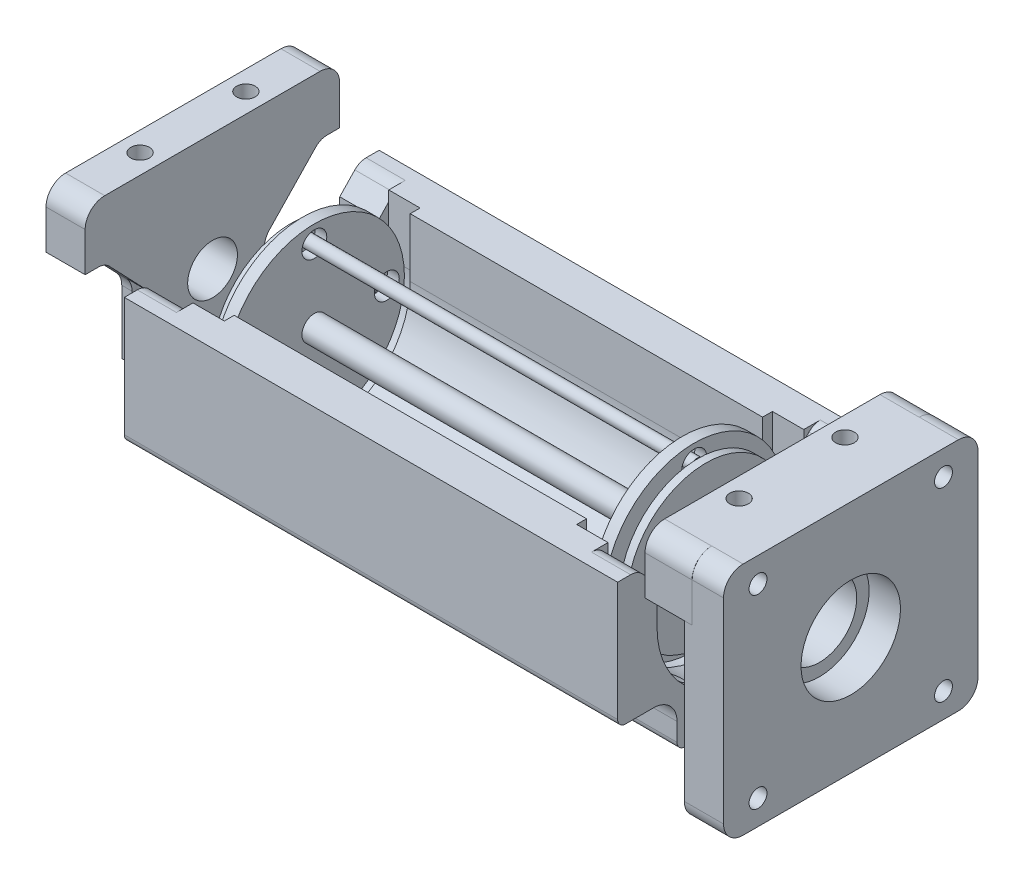
SolidWorks part; units mm, degrees
ref_plane "Front Plane" through (0, 0, 0) normal (0, 0, 1) x (1, 0, 0)
ref_plane "Top Plane" through (0, 0, 0) normal (0, 1, 0) x (1, 0, 0)
ref_plane "Right Plane" through (0, 0, 0) normal (1, 0, 0) x (0, 0, -1)
ref_plane "Plane1" through (-50, 0, 0) normal (1, 0, 0) x (0, 0, -1)
sketch "Sketch2" plane through (-50, 0, 0) normal (1, 0, 0) x (0, 0, -1)
  line L0 (0, 0) -> (0, 1.0694) construction
  circle A0 centre (0, 0) radius 3.175
  circle A1 centre (0, 18.5125) radius 1.5875 construction
  circle A2 centre (0, 18.5125) radius 3.175
  circle A3 centre (0, 0) radius 23
  circle A4 centre (-18.5125, 0) radius 1.5875 construction
  circle A5 centre (-18.5125, 0) radius 3.175
  circle A6 centre (0, -18.5125) radius 1.5875 construction
  circle A7 centre (0, -18.5125) radius 3.175
  circle A8 centre (18.5125, 0) radius 1.5875 construction
  circle A9 centre (18.5125, 0) radius 3.175
  dimension "D1" = 6.35
  dimension "D2" = 3.175
  dimension "D3" = 6.35
  dimension "D4" = 46
extrude "Boss-Extrude2" add sketch "Sketch2" along normal blind 3 separate body
ref_plane "Plane2" through (45, 0, 0) normal (1, 0, 0) x (0, 0, -1)
sketch "Sketch3" plane through (45, 0, 0) normal (1, 0, 0) x (0, 0, -1)
  line L0 (-22.4812, 0) -> (-22.4812, 15)
  line L1 (22.4812, 0) -> (22.4812, 15)
  line L2 (-23.371, -17.371) -> (-30.54, -17.371)
  line L3 (0, 0) -> (0, 31.7138) construction
  line L4 (-15.371, -30) -> (15.371, -30)
  line L5 (-17.371, -23.371) -> (-17.371, -28)
  line L6 (17.371, -23.371) -> (17.371, -28)
  line L7 (23.371, -17.371) -> (30, -17.371)
  line L8 (-32.54, 15) -> (-32.54, -15.371)
  line L9 (22.4812, 15) -> (32.54, 15)
  line L10 (-22.4812, 15) -> (-32.54, 15)
  line L11 (32.54, 15) -> (32.54, -15.371)
  line L13 (30.54, -17.371) -> (30, -17.371)
  arc A0 (-22.4812, 0) -> (22.4812, 0) centre (0, 0) ccw
  arc A1 (-23.371, -17.371) -> (-17.371, -23.371) centre (-23.371, -23.371) cw
  arc A2 (17.371, -23.371) -> (23.371, -17.371) centre (23.371, -23.371) cw
  arc A3 (-30.54, -17.371) -> (-32.54, -15.371) centre (-30.54, -15.371) cw
  arc A4 (32.54, -15.371) -> (30.54, -17.371) centre (30.54, -15.371) cw
  arc A5 (-17.371, -28) -> (-15.371, -30) centre (-15.371, -28) ccw
  arc A6 (17.371, -28) -> (15.371, -30) centre (15.371, -28) cw
  dimension "D1" = 6
  dimension "D2" = 6
  dimension "D3" = 2
  dimension "D4" = 2
  dimension "D5" = 2
extrude "Boss-Extrude3" add sketch "Sketch3" against normal blind 90 separate body
ref_plane "Plane9" through (-51, 0, 0) normal (1, 0, 0) x (0, 0, -1)
sketch "Sketch16" plane through (-51, 0, 0) normal (1, 0, 0) x (0, 0, -1)
  circle A1 centre (0, 0) radius 3.175
  circle A2 centre (0, 0) radius 20.1
  dimension "D1" = 6.35
extrude "Boss-Extrude7" add sketch "Sketch16" against normal blind 2 separate body
sketch "Sketch21" plane through (0, 0, 0) normal (1, 0, 0) x (0, 0, -1)
  circle A0 centre (-18.5125, 0) radius 1.5875
  circle A1 centre (0, 18.5125) radius 1.5875
  circle A2 centre (18.5125, 0) radius 1.5875
  circle A3 centre (0, -18.5125) radius 1.5875
  dimension "D1" = 4
extrude "Compression_Rods" add sketch "Sketch21" along normal mid plane 101.6 separate body
mirror "Mirror2" about plane through (0, 0, 0) normal (1, 0, 0) of bodies 102 113
ref_plane "Plane13" through (45, 0, 0) normal (1, 0, 0) x (0, 0, -1)
sketch "Sketch24" plane through (45, 0, 0) normal (1, 0, 0) x (0, 0, -1)
  line L0 (-25, 0) -> (-25, 15)
  line L1 (32.54, -15.371) -> (32.54, 15)
  line L2 (0, 0) -> (0, 36.0592) construction
  line L3 (-32.54, 15) -> (-25, 15)
  line L4 (-15.371, -30) -> (15.371, -30)
  line L5 (-17.371, -23.371) -> (-17.371, -28)
  line L6 (17.371, -23.371) -> (17.371, -28)
  line L7 (23.371, -17.371) -> (30.54, -17.371)
  line L8 (32.54, 15) -> (25, 15)
  line L9 (-32.54, -15.371) -> (-32.54, 15)
  line L10 (25, 0) -> (25, 15)
  line L13 (-23.371, -17.371) -> (-30.54, -17.371)
  arc A0 (-25, 0) -> (25, 0) centre (0, 0) ccw
  arc A1 (-17.371, -23.371) -> (-23.371, -17.371) centre (-23.371, -23.371) ccw
  arc A2 (17.371, -23.371) -> (23.371, -17.371) centre (23.371, -23.371) cw
  arc A3 (30.54, -17.371) -> (32.54, -15.371) centre (30.54, -15.371) ccw
  arc A4 (-30.54, -17.371) -> (-32.54, -15.371) centre (-30.54, -15.371) cw
  arc A5 (17.371, -28) -> (15.371, -30) centre (15.371, -28) cw
  arc A8 (-17.371, -28) -> (-15.371, -30) centre (-15.371, -28) ccw
  dimension "D1" = 6
  dimension "D2" = 6
  dimension "D3" = 2
  dimension "D4" = 2
extrude "Boss-Extrude13" add sketch "Sketch24" along normal blind 8 separate body
ref_plane "Plane15" through (70, 0, 0) normal (1, 0, 0) x (0, 0, -1)
sketch "Sketch27" plane through (70, 0, 0) normal (1, 0, 0) x (0, 0, -1)
  line L0 (-5.175, 30) -> (-25, 30)
  line L1 (23.6855, -23.6855) -> (-23.6855, -23.6855) construction
  line L2 (23.6855, -23.6855) -> (23.6855, 23.6855) construction
  line L3 (23.6855, 23.6855) -> (-23.6855, 23.6855) construction
  line L4 (-23.6855, -23.6855) -> (-23.6855, 23.6855) construction
  line L5 (23.6855, -23.6855) -> (-23.6855, 23.6855) construction
  line L6 (23.6855, 23.6855) -> (-23.6855, -23.6855) construction
  line L7 (5.175, 30) -> (25, 30)
  line L8 (-30, 25) -> (-30, -25)
  line L9 (-25, -30) -> (25, -30)
  line L10 (30, 25) -> (30, -25)
  line L11 (-30, 30) -> (30, -30) construction
  line L12 (-30, -30) -> (30, 30) construction
  line L13 (-3.175, 28) -> (-3.175, 20.404)
  line L14 (3.175, 28) -> (3.175, 20.404)
  line L15 (0, 0) -> (0, 18.7836) construction
  circle A0 centre (-23.6855, 23.6855) radius 2.286
  circle A1 centre (23.6855, 23.6855) radius 2.286
  circle A2 centre (-23.6855, -23.6855) radius 2.286
  circle A3 centre (23.6855, -23.6855) radius 2.286
  arc A4 (-19.05, 0) -> (19.05, 0) centre (0, 0) ccw
  arc A5 (-30, -25) -> (-25, -30) centre (-25, -25) ccw
  arc A6 (25, -30) -> (30, -25) centre (25, -25) ccw
  arc A7 (30, 25) -> (25, 30) centre (25, 25) ccw
  arc A8 (-30, 25) -> (-25, 30) centre (-25, 25) cw
  arc A9 (-19.05, 0) -> (-4.6833, 18.4653) centre (0, 0) cw
  arc A10 (19.05, 0) -> (4.6833, 18.4653) centre (0, 0) ccw
  arc A11 (-3.175, 20.404) -> (-4.6833, 18.4653) centre (-5.175, 20.404) cw
  arc A12 (3.175, 20.404) -> (4.6833, 18.4653) centre (5.175, 20.404) ccw
  arc A13 (3.175, 28) -> (5.175, 30) centre (5.175, 28) cw
  arc A14 (-3.175, 28) -> (-5.175, 30) centre (-5.175, 28) ccw
  point P0 (0, 0)
  point P10 (0, 0)
  point P37 (-3.175, 18.7836)
  point P40 (3.175, 18.7836)
  dimension "D3" = 5
  dimension "D1" = 2
  dimension "D2" = 60
  dimension "D5" = 60
extrude "Boss-Extrude17" add sketch "Sketch27" along normal blind 5 separate body
mirror "Mirror5" about plane through (0, 0, 0) normal (1, 0, 0) of bodies 127
sketch "Sketch28" plane through (0, 0, 0) normal (1, 0, 0) x (0, 0, -1)
  circle A0 centre (0, 0) radius 3.175
ref_plane "Plane16" through (80, 0, 0) normal (1, 0, 0) x (0, 0, -1)
ref_plane "Plane17" through (-75, 0, 0) normal (1, 0, 0) x (0, 0, -1)
sketch "Sketch34" plane through (-75, 0, 0) normal (1, 0, 0) x (0, 0, -1)
  line L0 (-25, 0) -> (-25, 18.5488)
  line L1 (25, 0) -> (25, 18.5488)
  line L2 (-23.371, -17.371) -> (-28, -17.371)
  line L3 (-30, 15) -> (-30, -15.371)
  line L4 (-15.371, -30) -> (15.371, -30)
  line L5 (-17.371, -23.371) -> (-17.371, -28)
  line L6 (17.371, -23.371) -> (17.371, -28)
  line L7 (23.371, -17.371) -> (28, -17.371)
  line L8 (21.7342, -9.525) -> (-21.7342, -9.525)
  line L9 (0, 0) -> (0, -13.7519) construction
  line L12 (30, -15.371) -> (30, 15)
  arc A0 (23.6241, -8.1793) -> (25, 0) centre (0, 0) ccw
  arc A1 (-23.371, -17.371) -> (-17.371, -23.371) centre (-23.371, -23.371) cw
  arc A2 (17.371, -23.371) -> (23.371, -17.371) centre (23.371, -23.371) cw
  arc A3 (-30, 15) -> (-25, 18.5488) centre (-26.2406, 15) cw
  arc A4 (30, 15) -> (25, 18.5488) centre (26.2406, 15) ccw
  arc A5 (-23.6241, -8.1793) -> (-21.7342, -9.525) centre (-21.7342, -7.525) ccw
  arc A6 (-23.6241, -8.1793) -> (-25, 0) centre (0, 0) cw
  arc A7 (-28, -17.371) -> (-30, -15.371) centre (-28, -15.371) cw
  arc A8 (23.6241, -8.1793) -> (21.7342, -9.525) centre (21.7342, -7.525) cw
  arc A9 (-17.371, -28) -> (-15.371, -30) centre (-15.371, -28) ccw
  arc A10 (17.371, -28) -> (15.371, -30) centre (15.371, -28) cw
  arc A11 (28, -17.371) -> (30, -15.371) centre (28, -15.371) ccw
  dimension "D1" = 6
  dimension "D2" = 6
  dimension "D3" = 2
  dimension "D4" = 2
extrude "Boss-Extrude22" add sketch "Sketch34" against normal blind 5 separate body
ref_plane "Plane18" through (53, 0, 0) normal (1, 0, 0) x (0, 0, -1)
sketch "Sketch37" plane through (53, 0, 0) normal (1, 0, 0) x (0, 0, -1)
  line L0 (-22.4812, 0) -> (-22.4812, 9.7374)
  line L1 (29.2208, 15) -> (32.54, 15)
  line L2 (-23.371, -17.371) -> (-30.54, -17.371)
  line L4 (-15.371, -30) -> (15.371, -30)
  line L5 (-17.371, -23.371) -> (-17.371, -28)
  line L6 (17.371, -23.371) -> (17.371, -28)
  line L7 (23.371, -17.371) -> (30, -17.371)
  line L8 (-32.54, 15) -> (-32.54, -15.371)
  line L9 (22.4812, 9.7374) -> (26.329, 13.7636)
  line L10 (-29.2208, 15) -> (-32.54, 15)
  line L11 (32.54, 15) -> (32.54, -15.371)
  line L12 (-22.4812, 9.7374) -> (-26.329, 13.7636)
  line L13 (30.54, -17.371) -> (30, -17.371)
  line L15 (22.4812, 0) -> (22.4812, 9.7374)
  arc A0 (-22.4812, 0) -> (22.4812, 0) centre (0, 0) ccw
  arc A1 (-23.371, -17.371) -> (-17.371, -23.371) centre (-23.371, -23.371) cw
  arc A2 (17.371, -23.371) -> (23.371, -17.371) centre (23.371, -23.371) cw
  arc A3 (-30.54, -17.371) -> (-32.54, -15.371) centre (-30.54, -15.371) cw
  arc A4 (32.54, -15.371) -> (30.54, -17.371) centre (30.54, -15.371) cw
  arc A5 (-17.371, -28) -> (-15.371, -30) centre (-15.371, -28) ccw
  arc A6 (17.371, -28) -> (15.371, -30) centre (15.371, -28) cw
  arc A7 (-26.329, 13.7636) -> (-29.2208, 15) centre (-29.2208, 11) ccw
  arc A8 (26.329, 13.7636) -> (29.2208, 15) centre (29.2208, 11) cw
  dimension "D1" = 6
  dimension "D2" = 6
  dimension "D3" = 2
  dimension "D4" = 2
  dimension "D5" = 2
  dimension "D6" = 4
extrude "Boss-Extrude27" add sketch "Sketch37" along normal blind 10
delete or keep bodies "Body-Delete1" type delete bodies bodies 144
delete or keep bodies "Body-Delete2" type delete bodies bodies 132
sketch "Sketch38" plane through (80, 0, 0) normal (1, 0, 0) x (0, 0, -1)
  line L1 (23.6855, -23.6855) -> (-23.6855, -23.6855) construction
  line L2 (23.6855, -23.6855) -> (23.6855, 23.6855) construction
  line L3 (23.6855, 23.6855) -> (-23.6855, 23.6855) construction
  line L4 (-23.6855, -23.6855) -> (-23.6855, 23.6855) construction
  line L5 (23.6855, -23.6855) -> (-23.6855, 23.6855) construction
  line L6 (23.6855, 23.6855) -> (-23.6855, -23.6855) construction
  line L7 (-27.5, 30) -> (27.5, 30)
  line L8 (-32.5, 25) -> (-32.5, -25)
  line L9 (-27.5, -30) -> (27.5, -30)
  line L10 (32.5, 25) -> (32.5, -25)
  line L11 (-32.5, 30) -> (32.5, -30) construction
  line L12 (-32.5, -30) -> (32.5, 30) construction
  circle A0 centre (-23.6855, 23.6855) radius 2.286
  circle A1 centre (23.6855, 23.6855) radius 2.286
  circle A2 centre (-23.6855, -23.6855) radius 2.286
  circle A3 centre (23.6855, -23.6855) radius 2.286
  circle A4 centre (0, 0) radius 12.7
  arc A5 (-32.5, -25) -> (-27.5, -30) centre (-27.5, -25) ccw
  arc A6 (27.5, -30) -> (32.5, -25) centre (27.5, -25) ccw
  arc A7 (32.5, 25) -> (27.5, 30) centre (27.5, 25) ccw
  arc A8 (-32.5, 25) -> (-27.5, 30) centre (-27.5, 25) cw
  point P0 (0, 0)
  point P10 (0, 0)
  dimension "D3" = 5
  dimension "D2" = 65
  dimension "D5" = 60
extrude "Boss-Extrude25" add sketch "Sketch38" along normal blind 10 separate body
ref_plane "Plane19" through (104, 0, 0) normal (1, 0, 0) x (0, 0, -1)
ref_plane "Plane20" through (83.426, 0, 0) normal (1, 0, 0) x (0, 0, -1)
ref_plane "Plane22" through (70, 0, 0) normal (1, 0, 0) x (0, 0, -1)
sketch "Sketch41" plane through (70, 0, 0) normal (1, 0, 0) x (0, 0, -1)
  line L0 (-29.2208, 15) -> (-32.54, 15)
  line L1 (-26.329, 13.7636) -> (-14.5758, 1.4654)
  line L2 (-32.54, 15) -> (-32.54, 25)
  line L3 (27.46, 30) -> (-27.54, 30)
  line L5 (13.1905, -1.9891) -> (13.1905, -18.2049)
  line L6 (-13.1905, -1.9891) -> (-13.1905, -18.2049)
  line L8 (32.46, 15) -> (29.2208, 15)
  line L9 (26.329, 13.7636) -> (14.5758, 1.4654)
  line L11 (32.46, 25) -> (32.46, 15)
  arc A0 (13.1905, -18.2049) -> (-13.1905, -18.2049) centre (0, 0) cw
  arc A1 (13.1905, -1.9891) -> (14.5758, 1.4654) centre (18.1905, -1.9891) cw
  arc A2 (-29.2208, 15) -> (-26.329, 13.7636) centre (-29.2208, 11) cw
  arc A3 (-14.5758, 1.4654) -> (-13.1905, -1.9891) centre (-18.1905, -1.9891) cw
  arc A4 (29.2208, 15) -> (26.329, 13.7636) centre (29.2208, 11) ccw
  arc A5 (-27.54, 30) -> (-32.54, 25) centre (-27.54, 25) ccw
  circle A6 centre (0, 0) radius 9.525
  arc A7 (32.46, 25) -> (27.46, 30) centre (27.46, 25) ccw
  circle A8 centre (23.6855, 23.6855) radius 2.286
  circle A9 centre (-23.6855, 23.6855) radius 2.286
  dimension "D1" = 5
  dimension "D3" = 19.05
  dimension "D5" = 5
  dimension "D6" = 5
  dimension "D2" = 4
  dimension "D4" = 5
extrude "Boss-Extrude29" add sketch "Sketch41" along normal blind 12 separate body
sketch "Sketch45" plane through (0, 30, 0) normal (0, 1, 0) x (1, 0, 0)
  circle A1 centre (75, -13.5137) radius 2.3813
extrude "Cut-Extrude4" cut sketch "Sketch45" against normal blind 50
mirror "Mirror10" about plane through (0, 0, 0) normal (0, 0, 1) of "Cut-Extrude4"
sketch "Sketch47" plane through (0, -30, 0) normal (0, -1, 0) x (1, 0, 0)
  circle A1 centre (58, -13.5137) radius 2.3812
extrude "Cut-Extrude5" cut sketch "Sketch47" against normal blind 50
mirror "Mirror11" about plane through (0, 0, 0) normal (0, 0, 1) of "Cut-Extrude5"
ref_plane "Plane23" through (-53, 0, 0) normal (1, 0, 0) x (0, 0, -1)
sketch "Sketch48" plane through (-53, 0, 0) normal (1, 0, 0) x (0, 0, -1)
  line L0 (-22.4812, 0) -> (-22.4812, 9.7374)
  line L1 (29.2208, 15) -> (32.54, 15)
  line L2 (-23.371, -17.371) -> (-30.54, -17.371)
  line L4 (-15.371, -30) -> (15.371, -30)
  line L5 (-17.371, -23.371) -> (-17.371, -28)
  line L6 (17.371, -23.371) -> (17.371, -28)
  line L7 (23.371, -17.371) -> (30, -17.371)
  line L8 (-32.54, 15) -> (-32.54, -15.371)
  line L9 (22.4812, 9.7374) -> (26.329, 13.7636)
  line L10 (-29.2208, 15) -> (-32.54, 15)
  line L11 (32.54, 15) -> (32.54, -15.371)
  line L12 (-22.4812, 9.7374) -> (-26.329, 13.7636)
  line L13 (30.54, -17.371) -> (30, -17.371)
  line L15 (22.4812, 0) -> (22.4812, 9.7374)
  arc A0 (-22.4812, 0) -> (22.4812, 0) centre (0, 0) ccw
  arc A1 (-23.371, -17.371) -> (-17.371, -23.371) centre (-23.371, -23.371) cw
  arc A2 (17.371, -23.371) -> (23.371, -17.371) centre (23.371, -23.371) cw
  arc A3 (-30.54, -17.371) -> (-32.54, -15.371) centre (-30.54, -15.371) cw
  arc A4 (32.54, -15.371) -> (30.54, -17.371) centre (30.54, -15.371) cw
  arc A5 (-17.371, -28) -> (-15.371, -30) centre (-15.371, -28) ccw
  arc A6 (17.371, -28) -> (15.371, -30) centre (15.371, -28) cw
  arc A7 (-26.329, 13.7636) -> (-29.2208, 15) centre (-29.2208, 11) ccw
  arc A8 (26.329, 13.7636) -> (29.2208, 15) centre (29.2208, 11) cw
  dimension "D1" = 6
  dimension "D2" = 6
  dimension "D3" = 2
  dimension "D4" = 2
  dimension "D5" = 2
  dimension "D6" = 4
extrude "Boss-Extrude30" add sketch "Sketch48" against normal blind 10 separate body
ref_plane "Plane24" through (-73, 0, 0) normal (1, 0, 0) x (0, 0, -1)
sketch "Sketch49" plane through (-73, 0, 0) normal (1, 0, 0) x (0, 0, -1)
  line L0 (-29.2208, 15) -> (-32.54, 15)
  line L1 (-26.329, 13.7636) -> (-14.5758, 1.4654)
  line L2 (-32.54, 15) -> (-32.54, 25)
  line L3 (27.46, 30) -> (-27.54, 30)
  line L4 (0, 0) -> (0, -22.4812) construction
  line L5 (13.1905, -1.9891) -> (13.1905, -18.2049)
  line L6 (-13.1905, -1.9891) -> (-13.1905, -18.2049)
  line L8 (32.46, 15) -> (29.2208, 15)
  line L9 (26.329, 13.7636) -> (14.5758, 1.4654)
  line L11 (32.46, 25) -> (32.46, 15)
  arc A0 (13.1905, -1.9891) -> (14.5758, 1.4654) centre (18.1905, -1.9891) cw
  arc A1 (-13.1905, -1.9891) -> (-14.5758, 1.4654) centre (-18.1905, -1.9891) ccw
  arc A2 (-29.2208, 15) -> (-26.329, 13.7636) centre (-29.2208, 11) cw
  arc A3 (13.1905, -18.2049) -> (-13.1905, -18.2049) centre (0, 0) cw
  arc A4 (29.2208, 15) -> (26.329, 13.7636) centre (29.2208, 11) ccw
  arc A5 (-27.54, 30) -> (-32.54, 25) centre (-27.54, 25) ccw
  circle A6 centre (0, 0) radius 6.35
  arc A7 (32.46, 25) -> (27.46, 30) centre (27.46, 25) ccw
  dimension "D1" = 5
  dimension "D3" = 12.7
  dimension "D5" = 5
  dimension "D6" = 5
  dimension "D2" = 4
  dimension "D4" = 5
extrude "Boss-Extrude31" add sketch "Sketch49" against normal blind 10 separate body
sketch "Sketch50" plane through (0, 30, 0) normal (0, 1, 0) x (1, 0, 0)
  circle A2 centre (-78, -13.5138) radius 2.3813
extrude "Cut-Extrude6" cut sketch "Sketch50" against normal blind 50
mirror "Mirror19" about plane through (0, 0, 0) normal (0, 0, 1) of "Cut-Extrude6"
sketch "Sketch51" plane through (0, -30, 0) normal (0, -1, 0) x (1, 0, 0)
  circle A2 centre (-58, 13.4937) radius 2.3812
extrude "Cut-Extrude7" cut sketch "Sketch51" against normal blind 50
mirror "Mirror20" about plane through (0, 0, 0) normal (0, 0, 1) of "Cut-Extrude7"
extrude "Boss-Extrude34" add sketch "Sketch28" along normal mid plane 127
combine bodies "Combine4" operation type add bodies to combine 164 149
sketch "Sketch55" plane through (70, 0, 0) normal (-1, 0, 0) x (0, 0, 1)
  line L0 (0, 0) -> (0, -22.4812)
ref_plane "Plane25" through (0, 0, -32.54) normal (0, 0, -1) x (-1, 0, 0)
sketch "Sketch65" plane through (0, 0, -32.54) normal (0, 0, -1) x (-1, 0, 0)
  line L0 (63, 9.525) -> (-63, 9.7374) construction
  line L1 (63, -15.371) -> (63, 15) construction
  line L2 (63, -9.525) -> (-63, -9.525) construction
  line L3 (-63, -15.371) -> (-63, 15) construction
  line L5 (-63, 9.7374) -> (63, 9.7374)
  line L6 (-63, 9.7374) -> (-63, -9.525)
  line L7 (-63, -9.525) -> (63, -9.525)
  line L8 (63, 9.7374) -> (63, -9.525)
  circle A0 centre (0, 0) radius 50.8 construction
  circle A1 centre (50.8, 0) radius 6.35
ref_plane "Plane27" through (0, 15, 0) normal (0, 1, 0) x (-1, 0, 0)
sketch "Sketch67" plane through (0, 15, 0) normal (0, 1, 0) x (-1, 0, 0)
  line L0 (-63, -32.54) -> (63, -32.54) construction
  line L1 (50.8, -32.54) -> (50.8, -38.89) construction
  line L2 (44.45, -35.715) -> (44.45, -42.065)
  line L3 (44.45, -42.065) -> (57.15, -42.065)
  line L4 (57.15, -42.065) -> (57.15, -35.715)
  circle A0 centre (0, -32.54) radius 50.8
  circle A1 centre (50.8, -35.715) radius 6.35
  circle A2 centre (50.8, -35.715) radius 3.9687
  dimension "D1" = 7.9375
